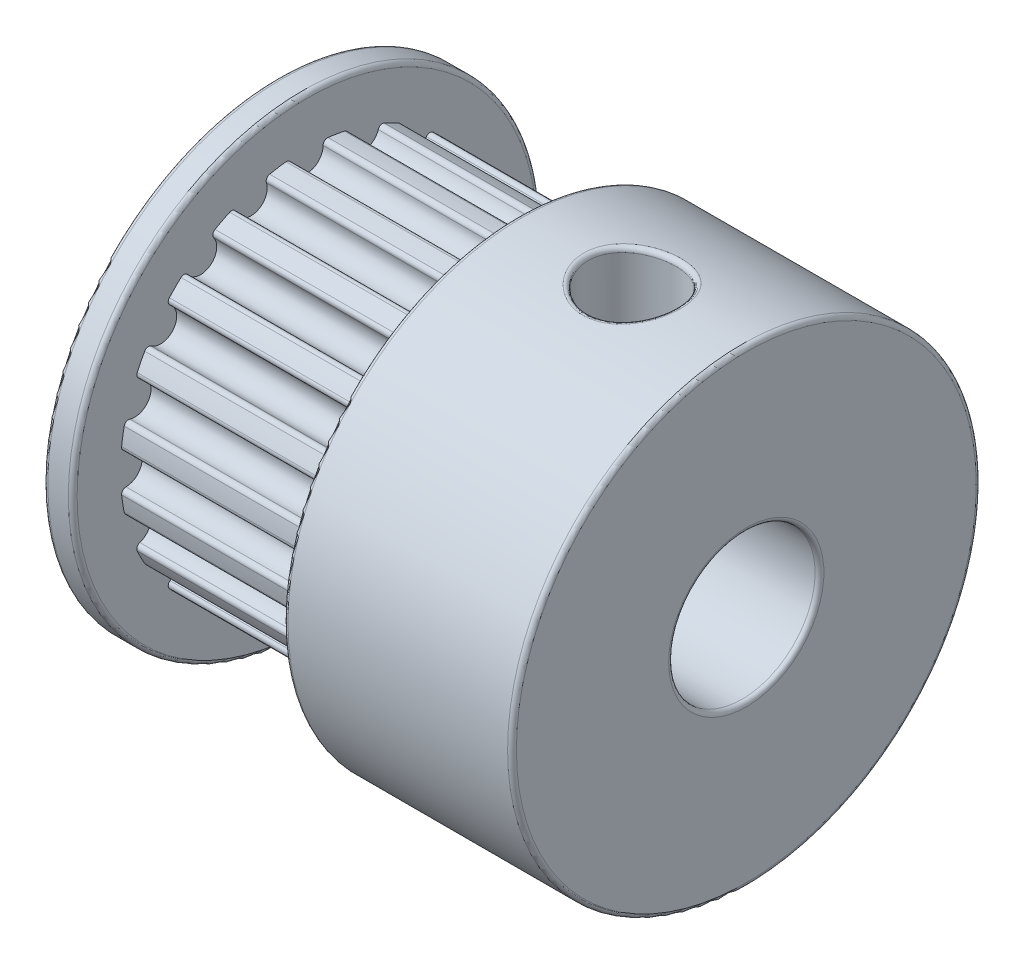
SolidWorks part; units mm, degrees
other "Camera1"
ref_plane "Front Plane" through (0, 0, 0) normal (0, 0, 1) x (1, 0, 0)
ref_plane "Top Plane" through (0, 0, 0) normal (0, 1, 0) x (1, 0, 0)
ref_plane "Right Plane" through (0, 0, 0) normal (1, 0, 0) x (0, 0, -1)
sketch "Sketch1" plane through (0, 0, 0) normal (0, 0, 1) x (1, 0, 0)
  line L1 (0, 0) -> (26.8238, 0) construction
  line L2 (0, 8) -> (1, 8)
  line L4 (0, 8) -> (0, 2.5)
  line L5 (0, 2.5) -> (16, 2.5)
  line L6 (1, 6.37) -> (8.2, 6.37)
  line L7 (8.2, 6.37) -> (8.2, 8)
  line L8 (8.2, 8) -> (16, 8)
  line L9 (16, 8) -> (16, 2.5)
  line L10 (1, 8) -> (1, 6.37)
  dimension "D1" = 8
  dimension "D2" = 1
  dimension "D3" = 5.5
  dimension "D4" = 2.5
  dimension "D5" = 7.2
  dimension "D6" = 7.8
  dimension "D7" = 16
revolve "Revolve1" add sketch "Sketch1" angle 360 about L1
sketch "Sketch2" plane through (8.2, 0, 0) normal (-1, 0, 0) x (0, 0, 1)
  line L0 (0, 6.37) -> (0, 6.18)
  arc A0 (0.5236, 6.3484) -> (-0.5236, 6.3484) centre (0, 0) ccw
  arc A1 (-0.5236, 6.3484) -> (0.5236, 6.3484) centre (0, 6.18) ccw
  dimension "D2" = 1.1
  dimension "D1" = 0.19
extrude "Cut-Extrude1" cut sketch "Sketch2" along normal blind 7.2 contours A1 A0
fillet "Fillet1" radius 0.15 2 edges at (4.6, 6.3484, -0.5236) (4.6, 6.3484, 0.5236)
pattern_circular "CirPattern1" count 20 over 360 about axis through (0, 0, 0) along (1, 0, 0) of "Fillet1", "Cut-Extrude1"
fillet "Fillet2" radius 0.15 5 edges at (0, 0, 8) (1, 0, 8) (8.2, 0, 8) (16, 0, 8) (0, 0, 2.5)
ref_plane "Plane1" through (0, 8, 0) normal (0, 1, 0) x (1, 0, 0)
sketch "Sketch3" plane through (0, 8, 0) normal (0, 1, 0) x (1, 0, 0)
  circle A0 centre (12.1, 0) radius 1.5
  point P5 (12.1, 0)
  point P9 (12.1, 0.9955)
  dimension "D1" = 3
extrude "Cut-Extrude2" cut sketch "Sketch3" against normal blind 7.2
fillet "Fillet3" radius 0.15 1 edges at (12.4158, 7.8645, -1.4664)
fillet "Fillet4" radius 0.15 1 edges at (16, 0, 2.5)
